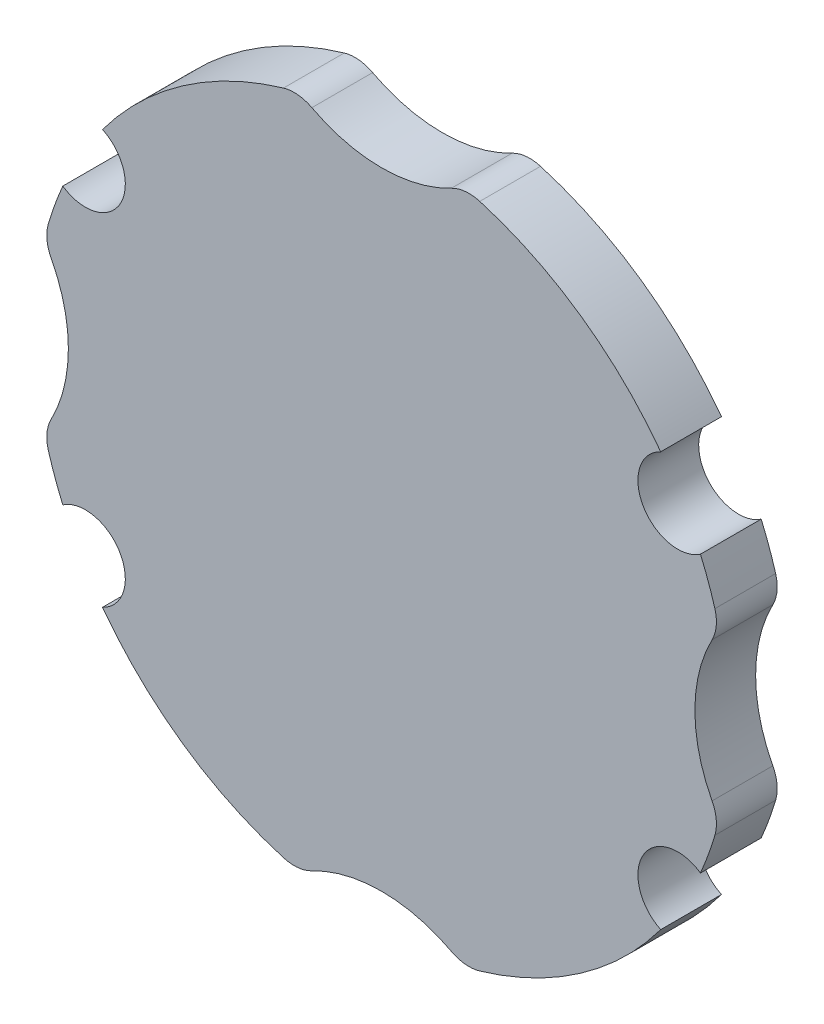
SolidWorks part; units mm, degrees
ref_plane "Front Plane" through (0, 0, 0) normal (0, 0, 1) x (1, 0, 0)
ref_plane "Top Plane" through (0, 0, 0) normal (0, 1, 0) x (1, 0, 0)
ref_plane "Right Plane" through (0, 0, 0) normal (1, 0, 0) x (0, 0, -1)
sketch "Sketch1" plane through (0, 0, 0) normal (0, 0, 1) x (1, 0, 0)
  arc A0 (2.1583, -8.8918) -> (8.8918, -2.1583) centre (0, 0) ccw
  arc A1 (8.8918, 2.1583) -> (8.8918, -2.1583) centre (12.2, 0) ccw
  arc A2 (8.8918, 2.1583) -> (2.1583, 8.8918) centre (0, 0) ccw
  arc A3 (-2.1583, 8.8918) -> (2.1583, 8.8918) centre (0, 12.2) ccw
  arc A4 (-2.1583, 8.8918) -> (-8.8918, 2.1583) centre (0, 0) ccw
  arc A5 (-8.8918, -2.1583) -> (-8.8918, 2.1583) centre (-12.2, 0) ccw
  arc A6 (-8.8918, -2.1583) -> (-2.1583, -8.8918) centre (0, 0) ccw
  arc A7 (2.1583, -8.8918) -> (-2.1583, -8.8918) centre (0, -12.2) ccw
  arc A8 (2.1197, -9.1066) -> (9.1066, -2.1197) centre (0, 0) ccw
  arc A9 (9.1066, 2.1197) -> (9.1066, -2.1197) centre (12.2, 0) ccw
  arc A10 (9.1066, 2.1197) -> (2.1197, 9.1066) centre (0, 0) ccw
  arc A11 (-2.1197, 9.1066) -> (2.1197, 9.1066) centre (0, 12.2) ccw
  arc A12 (-2.1197, 9.1066) -> (-9.1066, 2.1197) centre (0, 0) ccw
  arc A13 (-9.1066, -2.1197) -> (-9.1066, 2.1197) centre (-12.2, 0) ccw
  arc A14 (-9.1066, -2.1197) -> (-2.1197, -9.1066) centre (0, 0) ccw
  arc A15 (2.1197, -9.1066) -> (-2.1197, -9.1066) centre (0, -12.2) ccw
  arc A16 (2.1197, -9.1066) -> (9.1066, -2.1197) centre (0, 0) ccw construction
  arc A17 (9.1066, 2.1197) -> (9.1066, -2.1197) centre (12.2, 0) ccw construction
  arc A18 (9.1066, 2.1197) -> (2.1197, 9.1066) centre (0, 0) ccw construction
  arc A19 (-2.1197, 9.1066) -> (2.1197, 9.1066) centre (0, 12.2) ccw construction
  arc A20 (-2.1197, 9.1066) -> (-9.1066, 2.1197) centre (0, 0) ccw construction
  arc A21 (-9.1066, -2.1197) -> (-9.1066, 2.1197) centre (-12.2, 0) ccw construction
  arc A22 (-9.1066, -2.1197) -> (-2.1197, -9.1066) centre (0, 0) ccw construction
  arc A23 (2.1197, -9.1066) -> (-2.1197, -9.1066) centre (0, -12.2) ccw construction
  dimension "D1" = 0
  dimension "D2" = 0.2
extrude "Boss-Extrude1" add sketch "Sketch1" along normal blind 1.6
fillet "Fillet1" radius 1 8 edges at (-2.1583, -8.8918, 0.8) (-8.8918, -2.1583, 0.8) (-8.8918, 2.1583, 0.8) (-2.1583, 8.8918, 0.8) (8.8918, 2.1583, 0.8) (8.8918, -2.1583, 0.8) (2.1583, -8.8918, 0.8) (2.1583, 8.8918, 0.8)
sketch "Sketch2" plane through (0, 0, 1.6) normal (0, 0, 1) x (1, 0, 0)
  line L0 (0, 0) -> (9.15, 0) construction
  line L1 (0, 0) -> (0, 9.15) construction
  arc A0 (8.7773, 2.5849) -> (2.5849, 8.7773) centre (0, 0) ccw construction
  circle A1 centre (7.8, 4.5) radius 1.05
  circle A2 centre (7.8, -4.5) radius 1.05
  circle A3 centre (-7.8, -4.5) radius 1.05
  circle A4 centre (-7.8, 4.5) radius 1.05
  dimension "D1" = 2.1
  dimension "D2" = 9
  dimension "D3" = 15.6
extrude "Cut-Extrude1" cut sketch "Sketch2" against normal through all
